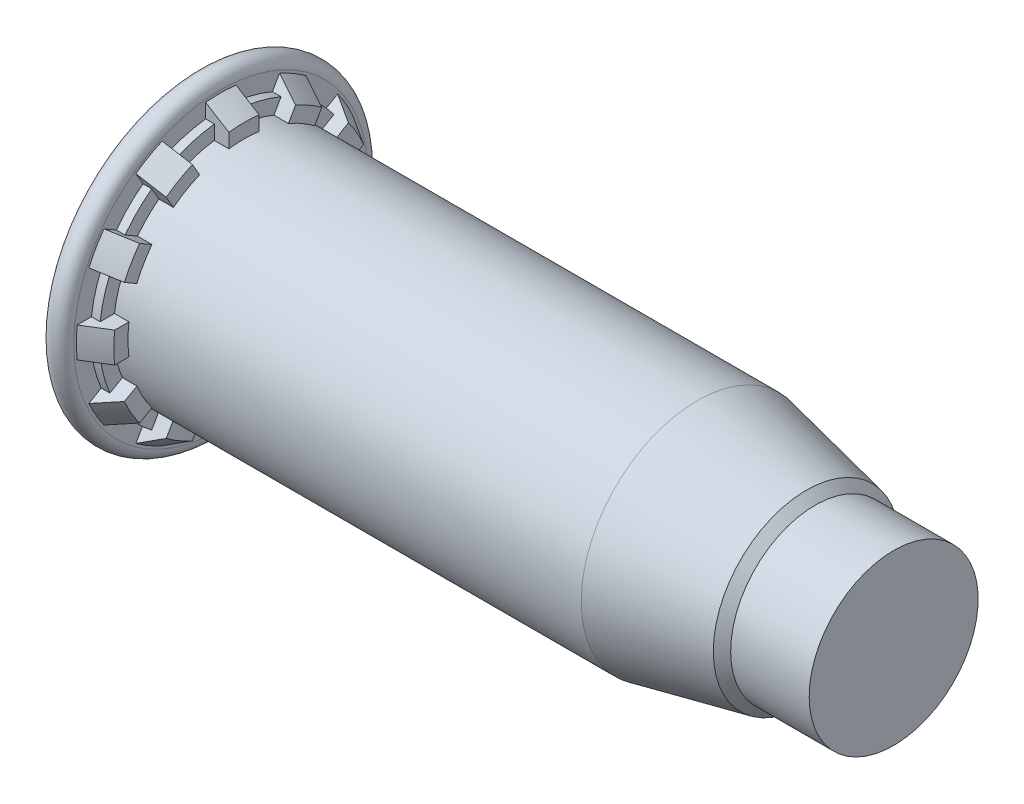
SolidWorks part; units mm, degrees
revolve "BaseBody" add sketch "BodySke" angle 360 about L6
sketch "BodySke" plane through (0, 0, 0) normal (0, 0, 1) x (1, 0, 0)
  line L0 (0, 0) -> (0, 3.7975)
  line L1 (0.6, 3.8025) -> (0.6, 3.735)
  line L2 (0.6, 3.735) -> (1.2, 3.3675)
  line L3 (1.2, 3) -> (12.92, 3)
  line L5 (18, 0) -> (0, 0)
  line L6 (0, 0) -> (50.554, 0) construction
  line L7 (1.2, 3.3675) -> (1.2, 3)
  line L8 (15.7455, 2.4095) -> (12.92, 3)
  line L9 (-9.525, 4.1) -> (9.525, 4.1) construction
  line L11 (2.2, 19.05) -> (2.2, -3.175) construction
  line L12 (18, 2.185) -> (18, 0)
  line L13 (9.525, -4.1) -> (-9.525, -4.1) construction
  line L14 (0.0051, 3.8025) -> (0.0051, 3.7975)
  line L15 (0, 3.7975) -> (0.0051, 3.7975)
  line L16 (15.97, 2.185) -> (18, 2.185)
  line L17 (15.7455, 2.4095) -> (15.97, 2.185)
  arc A0 (0.0051, 3.8025) -> (0.6, 3.8025) centre (0.3025, 3.8025) cw
  dimension "H_dia" = 8.2
  dimension "Shoulder_lower_dia" = 7.47
  dimension "Shoulder_upper_dia" = 6.735
  dimension "D1" = 0.0051
  dimension "D2" = 0.0051
  dimension "Shoulder_ht" = 1.2
  dimension "Advance" = 1
  dimension "Minor_dia" = 4.819
  dimension "Diameter" = 6
  dimension "T_dim" = 0.6
  dimension "Length" = 18
  dimension "Dog_dia" = 4.37
  dimension "Dog_len" = 2.03
  dimension "D5" = 45
  dimension "Thread_trans" = 3.05
cosmetic thread "ThreadCosmetic" [suppressed] parameters "Thread_length"=12.7455, "Thread_minor"=4.819
extrude "RibCut1" cut sketch "RibCut1Ske" against normal blind 0.375
sketch "RibCut1Ske" plane through (1.2, 0, 0) normal (1, 0, 0) x (0, 0, -1)
  line L0 (0.3916, 2.9743) -> (0.3916, 4.0813)
  line L1 (1.1481, 2.7716) -> (1.7015, 3.7303)
  line L2 (0, 0) -> (0, 4.9784) construction
  line L3 (0, 0) -> (0.3916, 2.9743) construction
  line L4 (0, 0) -> (1.1481, 2.7716) construction
  arc A1 (1.1481, 2.7716) -> (0.3916, 2.9743) centre (0, 0) ccw
  arc A2 (1.7015, 3.7303) -> (0.3916, 4.0813) centre (0, 0) ccw
  dimension "Angle" = 30
  dimension "Inner_dia" = 6
  dimension "Outer_dia" = 8.2
  dimension "Rib_root_half_angle" = 7.5
  dimension "Rib_root_gap_angle" = 15
ref_plane "Plane1" through (0, 0, 0) normal (0, 0, 1) x (1, 0, 0)
ref_plane "Plane2" through (0, 0, 0) normal (0, 1, 0) x (1, 0, 0)
ref_plane "Plane3" through (0, 0, 0) normal (1, 0, 0) x (0, 0, -1)
sketch "ThdSchSke" plane through (0, 0, 0) normal (0, 0, 1) x (1, 0, 0)
  line L0 (3, -2.4095) -> (2.5865, -3)
  line L1 (3, -2.4095) -> (3.4135, -3)
  line L2 (3.4135, -3) -> (3.4135, -3.75)
  line L3 (-3.175, 0) -> (5.1513, 0) construction
  line L5 (3.4135, -3.75) -> (2.5865, -3.75)
  line L6 (2.5865, -3.75) -> (2.5865, -3)
  line L7 (0, 3.7975) -> (0, -3.7975) construction
  dimension "Diameter" = 6
  dimension "SideAngle" = 55
  dimension "VeeAngle" = 70
  dimension "Thread_minor" = 4.819
  dimension "Overcut" = 7.5
  dimension "Start" = 3
revolve "ThreadSchematic" [suppressed] cut sketch "ThdSchSke" angle 360 about L3
pattern_linear "ThdSchPat" [suppressed]
sketch "RibCut2Ske" plane through (1.2, 0, 0) normal (1, 0, 0) x (0, 0, -1)
  line L0 (0.3916, 3.3447) -> (0.3916, 4.0813)
  line L1 (1.3332, 3.0923) -> (1.7015, 3.7303)
  line L2 (0.3916, 2.9743) -> (0.3916, 4.7861) construction
  line L3 (0, 0) -> (0, 5.0239) construction
  line L4 (0, 0) -> (0.3916, 2.9743) construction
  line L5 (0, 0) -> (1.1481, 2.7716) construction
  line L6 (1.1481, 2.7716) -> (2.0575, 4.3468) construction
  arc A1 (1.3332, 3.0923) -> (0.3916, 3.3447) centre (0, 0) ccw
  arc A2 (1.7015, 3.7303) -> (0.3916, 4.0813) centre (0, 0) ccw
  circle A4 centre (0, 0) radius 3 construction
  dimension "Angle" = 30
  dimension "Outer_dia" = 8.2
  dimension "Rib_root_half_angle" = 7.5
  dimension "Rib_root_gap_angle" = 15
extrude "RibCut2" cut sketch "RibCut2Ske" against normal blind 0.6
pattern_circular "RibCutsPat" count 12 every 30 about axis through (0, 0, 0) along (1, 0, 0) of "RibCut2", "RibCut1"
equation "' \"Length@BodySke\" = 18"
equation "' \"H_dia@BodySke\" = 8.2"
equation "' \"Start@ThdSchSke\" = 3"
equation "' \"Dog_dia@BodySke\" = 4.37"
equation "' \"Dog_len@BodySke\" = 2.03"
equation "' \"Thread_trans@BodySke\" = 3.05"
equation "' \"Diameter@BodySke\" = 6"
equation "' \"Minor_dia@BodySke\" = 4.819"
equation "' \"Advance@BodySke\" = 1"
equation "\"T_dim@BodySke\" = \"Start@ThdSchSke\" * 0.2"
equation "\"Shoulder_ht@BodySke\" = \"Start@ThdSchSke\" * 0.4"
equation "\"Shoulder_lower_dia@BodySke\" = \"H_dia@BodySke\" - \"Start@ThdSchSke\" * 0.2 - .13"
equation "\"Shoulder_upper_dia@BodySke\" = ( \"Shoulder_lower_dia@BodySke\" + \"Diameter@BodySke\" ) /2"
equation "\"Num_ribs@RibCutsPat\" = 12"
equation "\"Angle@RibCutsPat\" = 360 / \"Num_ribs@RibCutsPat\""
equation "\"Angle@RibCut1Ske\" =\"Angle@RibCutsPat\""
equation "\"Rib_root_half_angle@RibCut1Ske\" = \"Angle@RibCut1Ske\" / 4"
equation "\"Rib_root_gap_angle@RibCut1Ske\" = \"Angle@RibCut1Ske\" - (2 * \"Rib_root_half_angle@RibCut1Ske\" )"
equation "\"Inner_dia@RibCut1Ske\" = \"Diameter@BodySke\""
equation "\"Outer_dia@RibCut1Ske\" = \"H_dia@BodySke\""
equation "\"Depth@RibCut1\" =  \"Start@ThdSchSke\" * 0.125"
equation "\"Angle@RibCut2Ske\" =\"Angle@RibCutsPat\""
equation "\"Rib_root_half_angle@RibCut2Ske\" = \"Angle@RibCut1Ske\" / 4"
equation "\"Rib_root_gap_angle@RibCut2Ske\" = \"Angle@RibCut1Ske\" - (2 * \"Rib_root_half_angle@RibCut1Ske\" )"
equation "\"Rib_root_dia@RibCut2Ske\" = \"Diameter@BodySke\""
equation "\"Inner_dia@RibCut2Ske\" = \"Shoulder_upper_dia@BodySke\""
equation "\"Outer_dia@RibCut2Ske\" = \"H_dia@BodySke\""
equation "\"Depth@RibCut2\" =  \"Start@ThdSchSke\" * 0.2"
equation "\"Thread_length@ThreadCosmetic\" = \"Length@BodySke\" - \"Start@ThdSchSke\"  - \"Dog_len@BodySke\"  - ( \"Minor_dia@BodySke\" - \"Dog_dia@BodySke\" ) / 2"
equation "\"Thread_minor@ThreadCosmetic\" = \"Minor_dia@BodySke\""
equation "\"Thread_minor@ThdSchSke\" = \"Minor_dia@BodySke\""
equation "\"Diameter@ThdSchSke\" = \"Diameter@BodySke\""
equation "\"Overcut@ThdSchSke\" = \"Diameter@BodySke\" * 1.25"
equation "\"Num_threads@ThdSchPat\" = int( \"Thread_length@ThreadCosmetic\" / \"Advance@BodySke\" + 0.999 )  + 1"
equation "\"Advance@ThdSchPat\" = \"Thread_length@ThreadCosmetic\" /  (\"Num_threads@ThdSchPat\" - 1) 'relax it"
equation "\"Num_threads@ThdSchPat\" = \"Num_threads@ThdSchPat\" - sgn( \"Num_threads@ThdSchPat\" - 1) '---chamfered tips only---"
